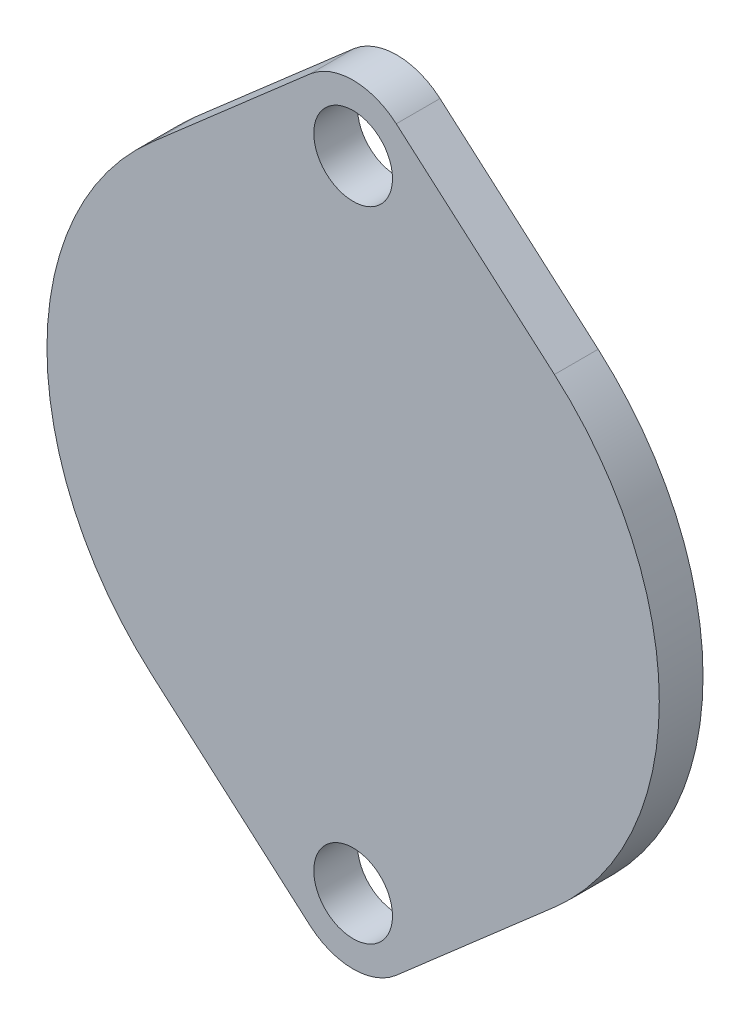
SolidWorks part; units mm, degrees
ref_plane "Front Plane" through (0, 0, 0) normal (0, 0, 1) x (1, 0, 0)
ref_plane "Top Plane" through (0, 0, 0) normal (0, 1, 0) x (1, 0, 0)
ref_plane "Right Plane" through (0, 0, 0) normal (1, 0, 0) x (0, 0, -1)
sketch "Sketch1" plane through (0, 0, 0) normal (0, 0, 1) x (1, 0, 0)
  line L0 (-4.9315, -42.1507) -> (-23.0137, -26.3699)
  line L1 (-23.0137, 26.3699) -> (-4.9315, 42.1507)
  line L2 (0, 0) -> (0, -9.7833) construction
  line L3 (4.9315, -42.1507) -> (23.0137, -26.3699)
  line L4 (23.0137, 26.3699) -> (4.9315, 42.1507)
  circle A0 centre (0, 0) radius 26.5 construction
  arc A1 (-23.0137, 26.3699) -> (-23.0137, -26.3699) centre (0, 0) ccw
  circle A2 centre (0, 36.5) radius 4.5
  circle A3 centre (0, -36.5) radius 4.5
  arc A4 (4.9315, 42.1507) -> (-4.9315, 42.1507) centre (0, 36.5) ccw
  arc A5 (-4.9315, -42.1507) -> (4.9315, -42.1507) centre (0, -36.5) ccw
  arc A6 (23.0137, -26.3699) -> (23.0137, 26.3699) centre (0, 0) ccw
  dimension "D1" = 53
  dimension "D2" = 9
  dimension "D3" = 9
  dimension "D5" = 70
  dimension "D7" = 15
  dimension "D8" = 15
  dimension "D4" = 36.5
  dimension "D6" = 36.5
extrude "Boss-Extrude1" add sketch "Sketch1" along normal blind 5
